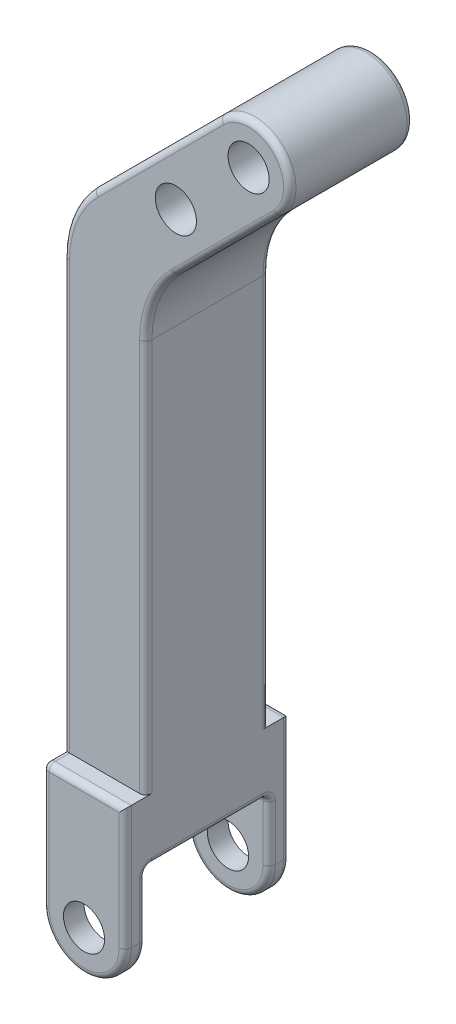
SolidWorks part; units mm, degrees
ref_plane "前视基准面" through (0, 0, 0) normal (0, 0, 1) x (1, 0, 0)
ref_plane "上视基准面" through (0, 0, 0) normal (0, 1, 0) x (1, 0, 0)
ref_plane "右视基准面" through (0, 0, 0) normal (1, 0, 0) x (0, 0, -1)
other "Configuration Table"
sketch "草图1" plane through (0, 0, 0) normal (0, 0, 1) x (1, 0, 0)
  circle A0 centre (0, 0) radius 20
  circle A1 centre (0, 0) radius 10
  dimension "D1" = 40
  dimension "D2" = 20
extrude "凸台-拉伸1" add sketch "草图1" along normal blind 60 contours A1 | A0
ref_plane "基准面1" through (0, 0, 30) normal (0, 0, 1) x (1, 0, 0)
sketch "草图2" plane through (0, 0, 30) normal (0, 0, 1) x (1, 0, 0)
  line L0 (0, 0) -> (-70, -70) construction
  line L1 (-70, -70) -> (-70, -320) construction
  line L2 (0, -57.3148) -> (0, 49.9409) construction
  line L3 (-56.8582, 0) -> (46.4003, 0) construction
  line L4 (-14.1421, 14.1421) -> (-90, -61.7157)
  line L5 (14.1421, -14.1421) -> (-50, -78.2843)
  line L6 (-90, -61.7157) -> (-90, -320)
  line L7 (-50, -78.2843) -> (-50, -320)
  line L8 (-90, -320) -> (-50, -320)
  circle A2 centre (0, 0) radius 20 construction
  arc A3 (-14.1421, 14.1421) -> (14.1421, -14.1421) centre (0, 0) ccw
  dimension "D1" = 45
  dimension "D2" = 250
  dimension "D3" = 70
  dimension "D4" = 40
  dimension "D5" = 40
extrude "凸台-拉伸2" add sketch "草图2" along normal mid plane 60 contours L7 L8 L6 L4 A3 L5
sketch "草图4" plane through (0, 0, 60) normal (0, 0, 1) x (1, 0, 0)
  line L0 (-90, -61.7157) -> (-90, -320) construction
  line L1 (-90, -290) -> (-50, -290)
  line L2 (-90, -290) -> (-90, -350)
  line L4 (-50, -290) -> (-50, -350)
  line L5 (-50, -78.2843) -> (-50, -320) construction
  line L6 (-90, -320) -> (-50, -320) construction
  arc A0 (-90, -350) -> (-50, -350) centre (-70, -350) ccw
  circle A1 centre (-70, -350) radius 10
  dimension "D3" = 20
  dimension "D1" = 30
  dimension "D2" = 30
extrude "凸台-拉伸3" add sketch "草图4" along normal blind 10
mirror "镜向1" about plane through (0, 0, 30) normal (0, 0, 1) of "凸台-拉伸3"
sketch "草图5" plane through (0, 0, 0) normal (0, 1, 0) x (1, 0, 0)
  line L0 (0, 0) -> (0, -78.0582) construction
ref_plane "基准面2" through (-70, 0, 0) normal (-1, 0, 0) x (0, 0, 1)
sketch "草图7" plane through (-70, 0, 0) normal (-1, 0, 0) x (0, 0, 1)
  line L0 (-34.1239, -350) -> (109.535, -350) construction
sketch "草图8" plane through (0, 0, 60) normal (0, 0, 1) x (1, 0, 0)
  line L0 (0, 0) -> (-70, -70) construction
  circle A0 centre (-35.3553, -35.3553) radius 10
  dimension "D1" = 20
  dimension "D2" = 50
extrude "切除-拉伸1" cut sketch "草图8" against normal blind 100
fillet "圆角1" radius 50 2 edges at (-90, -61.7157, 30) (-50, -78.2843, 30)
fillet "圆角2" radius 3 34 edges at (-50, -320, 70) (-70, -370, 70) (-50, -335, 60) (-70, -370, 60) (-90, -335, 0) (-50, -335, 0) (-70, -370, 0) (-90, -320, -10) (-50, -320, -10) (-70, -370, -10) (-70, -320, 60) (-50, -320, 30) (-70, -320, 0) (-90, -290, 65) (-90, -320, 70) (-90, -335, 60) (-90, -320, 30) (-90, -290, -5) (-50, -194.4975, 0) (-46.194, -79.8608, 0) (-10.6066, -38.8909, 60) (-10.6066, -38.8909, 0) (14.1421, 14.1421, 0) (-44.7487, -16.4645, 0) (-44.7487, -16.4645, 60) (-86.194, -63.2922, 0) (-90, -186.2132, 0) (14.1421, 14.1421, 60) (-46.194, -79.8608, 60) (-50, -194.4975, 60) (-90, -186.2132, 60) (-86.194, -63.2922, 60) (-70, -290, 70) (-70, -290, -10)
